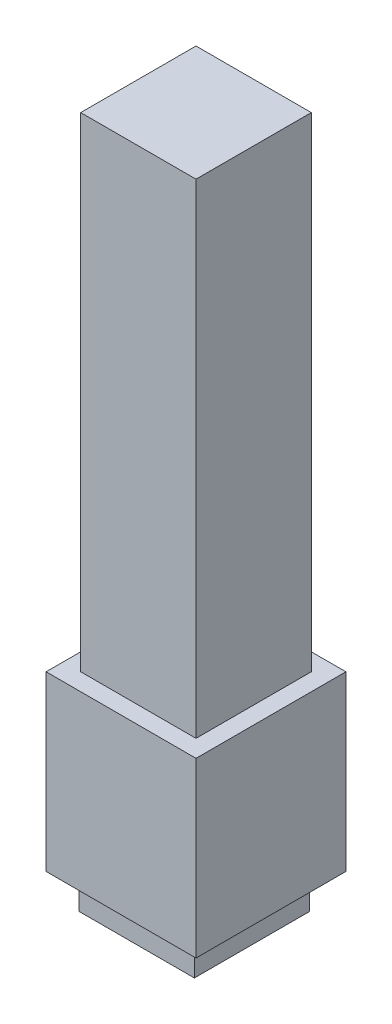
SolidWorks part; units mm, degrees
ref_plane "Front Plane" through (0, 0, 0) normal (0, 0, 1) x (1, 0, 0)
ref_plane "Top Plane" through (0, 0, 0) normal (0, 1, 0) x (1, 0, 0)
ref_plane "Right Plane" through (0, 0, 0) normal (1, 0, 0) x (0, 0, -1)
sketch "Sketch1" plane through (0, 0, 0) normal (0, 1, 0) x (1, 0, 0)
  line L1 (0, 0) -> (508, 0)
  line L2 (0, 0) -> (0, 508)
  line L3 (0, 508) -> (508, 508)
  line L4 (508, 0) -> (508, 508)
  line L5 (0, 0) -> (508, 508) construction
  line L6 (0, 508) -> (508, 0) construction
  point P4 (254, 254)
  dimension "D1" = 508
  dimension "D2" = 508
extrude "Boss-Extrude1" add sketch "Sketch1" along normal blind 152.4
sketch "Sketch2" plane through (0, 152.4, 0) normal (0, 1, 0) x (1, 0, 0)
  line L0 (0, 0) -> (508, 508) construction
  line L1 (508, 508) -> (257.591, 257.591) construction
  line L2 (257.591, 257.591) -> (0, 508) construction
  line L3 (0, 0) -> (508, 0) construction
  line L4 (-72.609, -72.609) -> (587.791, -72.609)
  line L5 (-72.609, -72.609) -> (-72.609, 587.791)
  line L6 (-72.609, 587.791) -> (587.791, 587.791)
  line L7 (587.791, -72.609) -> (587.791, 587.791)
  line L8 (-72.609, -72.609) -> (587.791, 587.791) construction
  line L9 (-72.609, 587.791) -> (587.791, -72.609) construction
  dimension "D1" = 660.4
  dimension "D2" = 660.4
  dimension "D3" = 257.591
extrude "Boss-Extrude2" add sketch "Sketch2" along normal blind 762
sketch "Sketch3" plane through (0, 914.4, 0) normal (0, 1, 0) x (1, 0, 0)
  line L0 (-72.609, -72.609) -> (587.791, 587.791) construction
  line L1 (257.591, 257.591) -> (-72.609, 257.591) construction
  line L2 (-72.609, 587.791) -> (-72.609, -72.609) construction
  line L4 (3.591, 3.591) -> (511.591, 3.591)
  line L5 (3.591, 3.591) -> (3.591, 511.591)
  line L6 (3.591, 511.591) -> (511.591, 511.591)
  line L7 (511.591, 3.591) -> (511.591, 511.591)
  line L8 (3.591, 3.591) -> (511.591, 511.591) construction
  line L9 (3.591, 511.591) -> (511.591, 3.591) construction
  dimension "D1" = 508
  dimension "D2" = 508
extrude "Boss-Extrude3" add sketch "Sketch3" along normal blind 2133.6
